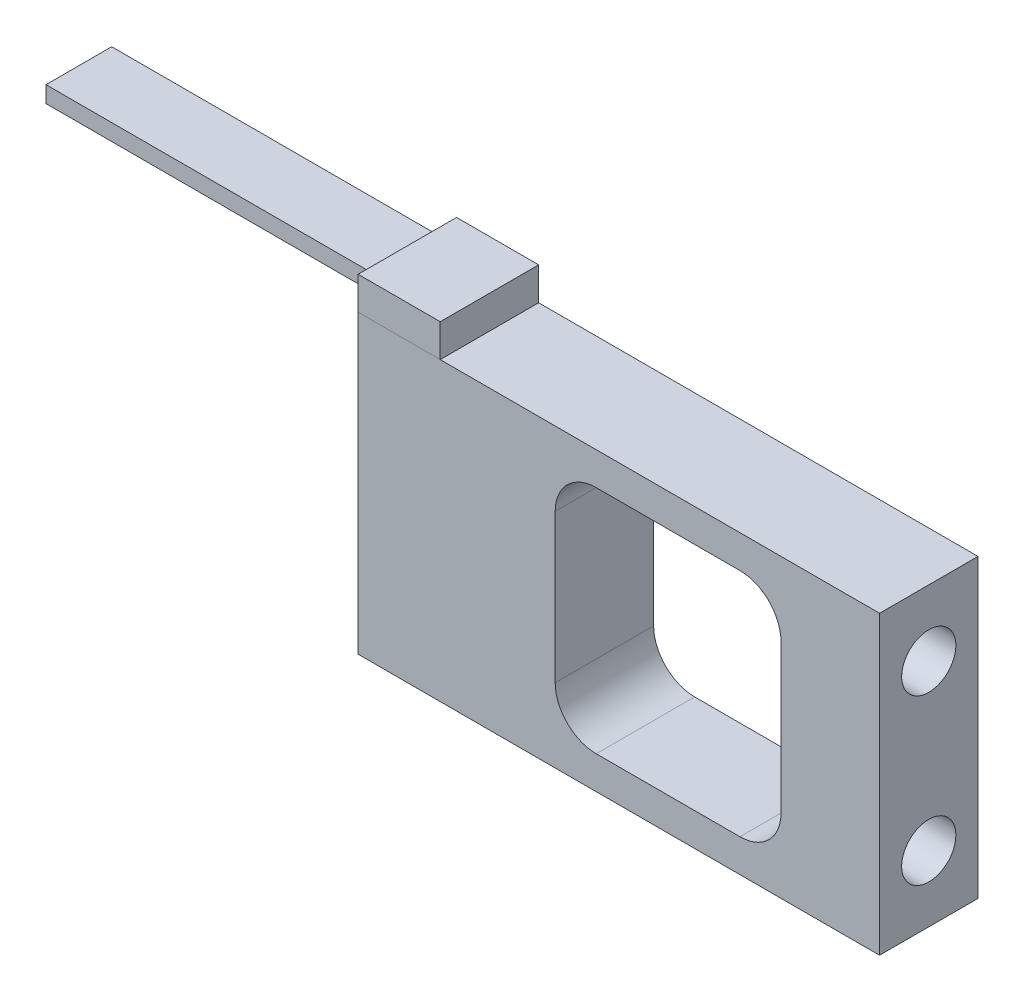
SolidWorks part; units mm, degrees
material "AISI 316 Annealed Stainless Steel Bar (SS)"
ref_plane "Front Plane" through (0, 0, 0) normal (0, 0, 1) x (1, 0, 0)
ref_plane "Top Plane" through (0, 0, 0) normal (0, 1, 0) x (1, 0, 0)
ref_plane "Right Plane" through (0, 0, 0) normal (1, 0, 0) x (0, 0, -1)
sketch "Sketch1" plane through (0, 0, 0) normal (0, 0, 1) x (1, 0, 0)
  line L1 (15.875, -9.017) -> (-15.875, -9.017)
  line L2 (15.875, -9.017) -> (15.875, 9.017)
  line L3 (15.875, 9.017) -> (-15.875, 9.017)
  line L4 (-15.875, -9.017) -> (-15.875, 9.017)
  line L5 (15.875, -9.017) -> (-15.875, 9.017) construction
  line L6 (15.875, 9.017) -> (-15.875, -9.017) construction
  point P0 (0, 0)
  dimension "D1" = 31.75
  dimension "D2" = 18.034
extrude "Boss-Extrude1" add sketch "Sketch1" along normal mid plane 5.9944
sketch "Sketch8" plane through (0, 0, 2.9972) normal (0, 0, 1) x (1, 0, 0)
  line L0 (15.875, 9.017) -> (-15.875, 9.017) construction
  line L1 (9.875, -7.017) -> (-3.875, -7.017)
  line L2 (9.875, -7.017) -> (9.875, 7.017)
  line L3 (9.875, 7.017) -> (-3.875, 7.017)
  line L4 (-3.875, -7.017) -> (-3.875, 7.017)
  line L5 (9.875, -7.017) -> (-3.875, 7.017) construction
  line L6 (9.875, 7.017) -> (-3.875, -7.017) construction
  line L7 (15.875, -9.017) -> (15.875, 9.017) construction
  line L8 (-15.875, 9.017) -> (-15.875, -9.017) construction
  point P0 (3, 0)
  dimension "D1" = 2
  dimension "D2" = 6
  dimension "D3" = 12
extrude "Cut-Extrude3" cut sketch "Sketch8" against normal through all
fillet "Fillet1" radius 2.5 4 edges at (9.875, 7.017, 0) (9.875, -7.017, 0) (-3.875, -7.017, 0) (-3.875, 7.017, 0)
hole_wizard "M4 Tapped Hole1" positions "Sketch2" profile "Sketch3" tap size "M4" standard "ISO"
sketch "Sketch2" plane through (15.875, 0, 0) normal (1, 0, 0) x (0, 0, -1)
  line L0 (0, -5) -> (0, 5) construction
  point P0 (0, 5)
  point P2 (0, -5)
  dimension "D1" = 10
sketch "Sketch3" plane through (15.875, 5, 0) normal (0, 1, 0) x (0, 0, -1)
  line L0 (0, 0) -> (0, 10.4914)
  line L1 (0, 10.4914) -> (1.65, 9.5)
  line L2 (1.65, 9.5) -> (1.65, 0)
  line L5 (1.65, 0) -> (0, 0)
  line L10 (0, 10.4914) -> (-1.65, 9.5) construction
  line L11 (0, -6.35) -> (0, 107.95) construction
  dimension "Tap Drill Dia." = 3.3
  dimension "Tap Drill Depth" = 9.5
  dimension "Drill Angle" = 118
cosmetic thread "Hole Thread1" parameters "D1"=6, "D2"=4
cosmetic thread "Hole Thread2" parameters "D1"=6, "D2"=4
mirror "Mirror1" about plane through (0, 0, 0) normal (1, 0, 0) of "M4 Tapped Hole1"
sketch "Sketch4" plane through (0, 0, 0) normal (0, 0, 1) x (1, 0, 0)
  circle A0 centre (0, 0) radius 7.5
  dimension "D1" = 15
extrude "Cut-Extrude1" [suppressed] cut sketch "Sketch4" against normal through all both and the other way through all
sketch "Sketch5" plane through (0, 0, 0) normal (0, 0, 1) x (1, 0, 0)
  line L0 (0, 0) -> (-6.8944, 5.7851) construction
  line L1 (0, -1000) -> (0, 49000) construction
  circle A0 centre (-6.8944, 5.7851) radius 2.5
  dimension "D1" = 50
  dimension "D3" = 5
  dimension "D2" = 9
extrude "Cut-Extrude2" [suppressed] cut sketch "Sketch5" against normal through all both and the other way through all
mirror "Mirror2" [suppressed] about plane through (0, 0, 0) normal (0, 1, 0)
mirror "Mirror3" [suppressed] about plane through (0, 0, 0) normal (1, 0, 0)
sketch "Sketch6" plane through (0, 9.017, 0) normal (0, 1, 0) x (1, 0, 0)
  line L0 (15.875, 2.9972) -> (-15.875, 2.9972) construction
  line L1 (-15.875, -2.9972) -> (-10.875, -2.9972)
  line L2 (-15.875, -2.9972) -> (-15.875, 2.9972)
  line L3 (-15.875, 2.9972) -> (-10.875, 2.9972)
  line L4 (-10.875, -2.9972) -> (-10.875, 2.9972)
  line L5 (-15.875, -2.9972) -> (-10.875, 2.9972) construction
  line L6 (-15.875, 2.9972) -> (-10.875, -2.9972) construction
  point P4 (-13.375, 0)
  dimension "D1" = 5
extrude "Boss-Extrude2" add sketch "Sketch6" along normal blind 2 separate body
sketch "Sketch7" plane through (-15.875, 0, 0) normal (-1, 0, 0) x (0, 0, 1)
  line L0 (0, 11.017) -> (0, 9.017) construction
  line L1 (2, 10.517) -> (-2, 10.517)
  line L2 (2, 10.517) -> (2, 9.517)
  line L3 (2, 9.517) -> (-2, 9.517)
  line L4 (-2, 10.517) -> (-2, 9.517)
  line L5 (2, 10.517) -> (-2, 9.517) construction
  line L6 (2, 9.517) -> (-2, 10.517) construction
  line L7 (-2.9972, 11.017) -> (2.9972, 11.017) construction
  line L8 (2.9972, 9.017) -> (-2.9972, 9.017) construction
  point P0 (0, 10.017)
  dimension "D1" = 1
  dimension "D2" = 4
extrude "Boss-Extrude3" add sketch "Sketch7" along normal blind 20
